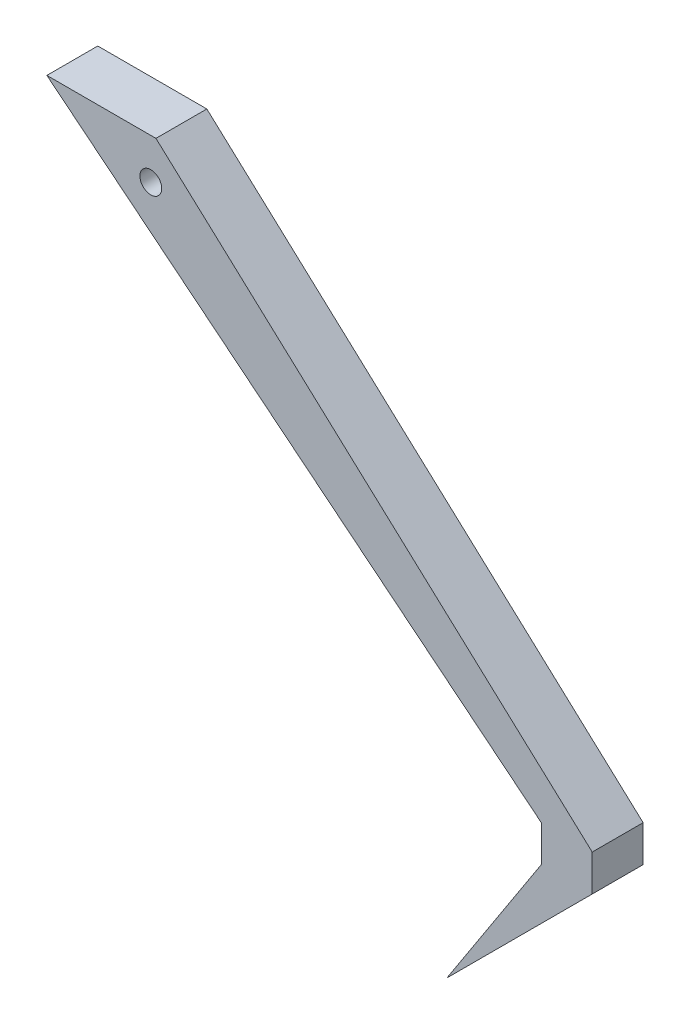
SolidWorks part; units mm, degrees
ref_plane "Front Plane" through (0, 0, 0) normal (0, 0, 1) x (1, 0, 0)
ref_plane "Top Plane" through (0, 0, 0) normal (0, 1, 0) x (1, 0, 0)
ref_plane "Right Plane" through (0, 0, 0) normal (1, 0, 0) x (0, 0, -1)
sketch "Sketch1" plane through (0, 0, 0) normal (0, 0, 1) x (1, 0, 0)
  line L0 (0, 0) -> (60, 0) construction
  line L1 (60, 0) -> (60, -55) construction
  line L2 (60, -55) -> (53, -55) construction
  line L3 (0, 0) -> (60, -55)
  line L4 (0, 0) -> (-15, 0) construction
  line L5 (-15, 0) -> (53, -55)
  line L6 (-15, 0) -> (0, 0)
  line L7 (60, -55) -> (60, -60)
  line L8 (53, -55) -> (53, -60)
  line L9 (60, -60) -> (60, -80) construction
  line L10 (60, -80) -> (40, -80) construction
  line L11 (60, -60) -> (40, -80)
  line L12 (40, -80) -> (53, -60)
  dimension "D1" = 60
  dimension "D2" = 55
  dimension "D3" = 7
  dimension "D4" = 15
  dimension "D5" = 5
  dimension "D6" = 20
  dimension "D7" = 20
extrude "Boss-Extrude1" add sketch "Sketch1" along normal blind 7 contours L12 L8 L5 L6 L3 L7 L11
sketch "Sketch2" plane through (0, 0, 7) normal (0, 0, 1) x (1, 0, 0)
  circle A1 centre (-0.7056, -5.5821) radius 1.5
extrude "Cut-Extrude3" cut sketch "Sketch2" against normal mid plane 15
